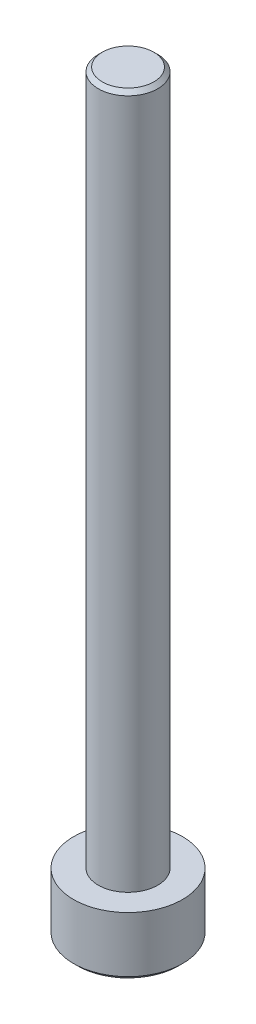
SolidWorks part; units mm, degrees
ref_plane "Front Plane" through (0, 0, 0) normal (0, 0, 1) x (1, 0, 0)
ref_plane "Top Plane" through (0, 0, 0) normal (0, 1, 0) x (1, 0, 0)
ref_plane "Right Plane" through (0, 0, 0) normal (1, 0, 0) x (0, 0, -1)
sketch "Reconstructed nominal axial profile" plane through (0, 0, 0) normal (0, 0, 1) x (1, 0, 0)
  line L0 (0, -500) -> (0, 50) construction
  line L1 (0, -3) -> (2.55, -3)
  line L2 (2.55, -3) -> (2.75, -2.8)
  line L3 (2.75, -2.8) -> (2.75, 0)
  line L4 (2.75, 0) -> (1.5, 0)
  line L5 (1.5, 0) -> (1.5, 34.8)
  line L6 (1.5, 34.8) -> (1.3, 35)
  line L7 (1.3, 35) -> (0, 35)
  line L8 (0, 35) -> (0, -3)
revolve "Native revolved geometry" add sketch "Reconstructed nominal axial profile" angle 360 about L0
sketch "Sketch2" plane through (0, 0, 0) normal (0, 1, 0) x (1, 0, 0)
  line L0 (1.4434, 0) -> (0.7217, -1.25)
  line L1 (0.7217, -1.25) -> (-0.7217, -1.25)
  line L2 (-0.7217, -1.25) -> (-1.4434, 0)
  line L3 (-1.4434, 0) -> (-0.7217, 1.25)
  line L4 (-0.7217, 1.25) -> (0.7217, 1.25)
  line L5 (0.7217, 1.25) -> (1.4434, 0)
extrude "Simplified nominal hex socket" cut sketch "Sketch2" along normal blind 1.5 from offset 3
